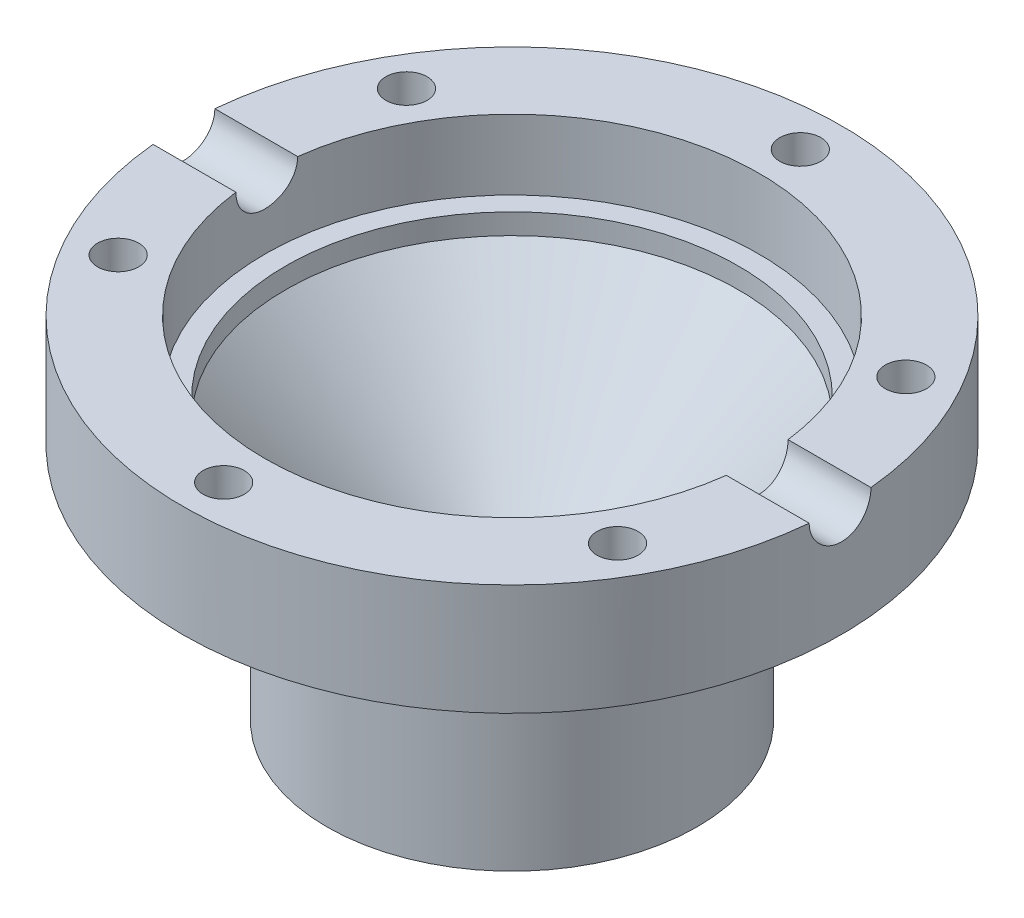
SolidWorks part; units mm, degrees
ref_plane "Front Plane" through (0, 0, 0) normal (0, 0, 1) x (1, 0, 0)
ref_plane "Top Plane" through (0, 0, 0) normal (0, 1, 0) x (1, 0, 0)
ref_plane "Right Plane" through (0, 0, 0) normal (1, 0, 0) x (0, 0, -1)
ref_axis "Centerline" through (0, 55, 0) along (0, -1, 0)
sketch "Sketch1" plane through (0, 0, 0) normal (0, 1, 0) x (1, 0, 0)
  circle A0 centre (0, 0) radius 20.32
  dimension "D1" = 40.64
extrude "Boss-Extrude1" add sketch "Sketch1" along normal blind 21.59
sketch "Sketch2" plane through (0, 0, 0) normal (0, 0, 1) x (1, 0, 0)
  line L0 (0, 26.2246) -> (0, -7.0612) construction
  line L5 (20.32, 21.59) -> (-20.32, 21.59) construction
  line L6 (0, 21.59) -> (-15.24, 21.59)
  line L7 (0, 21.59) -> (0, 17.272)
  line L8 (0, 17.272) -> (-15.24, 17.272)
  line L9 (-15.24, 21.59) -> (-15.24, 17.272)
  line L10 (-20.32, 21.59) -> (-20.32, 0) construction
  dimension "D1" = 5.08
  dimension "D2" = 4.318
revolve "Cut-Revolve1" cut sketch "Sketch2" angle 360 about axis through (0, 55, 0) along (0, -1, 0)
sketch "Sketch3" plane through (0, 0, 0) normal (0, 0, 1) x (1, 0, 0)
  line L0 (-20.32, 0) -> (20.32, 0) construction
  line L1 (-20.32, 14.732) -> (-15.24, 14.732)
  line L2 (-20.32, 14.732) -> (-20.32, 0)
  line L3 (-20.32, 0) -> (-15.24, 0)
  line L4 (-15.24, 14.732) -> (-15.24, 0)
  line L5 (20.32, 21.59) -> (-20.32, 21.59) construction
  line L6 (-20.32, 21.59) -> (-20.32, 0) construction
  dimension "D1" = 6.858
  dimension "D2" = 5.08
revolve "Cut-Revolve2" cut sketch "Sketch3" angle 360 about axis through (0, 55, 0) along (0, -1, 0)
sketch "Sketch4" plane through (0, 21.59, 0) normal (0, 1, 0) x (1, 0, 0)
  line L0 (0, 29.0947) -> (0, -35.1526) construction
  circle A0 centre (0, 17.78) radius 1.27
  dimension "D1" = 2.54
  dimension "D2" = 17.78
extrude "Cut-Extrude1" cut sketch "Sketch4" against normal up to next
pattern_circular "CirPattern1" count 6 over 360 about axis through (0, 0, 0) along (0, 1, 0) of "Cut-Extrude1"
sketch "Sketch5" plane through (0, 0, 0) normal (0, -1, 0) x (1, 0, 0)
  circle A0 centre (0, 0) radius 4.699
  dimension "D1" = 9.398
extrude "Cut-Extrude2" cut sketch "Sketch5" against normal up to next
sketch "Sketch7" plane through (0, 0, 0) normal (0, 0, 1) x (1, 0, 0)
  line L0 (-19.3213, 14.732) -> (23.1214, 14.732) construction
  line L1 (-20.32, 14.732) -> (20.32, 14.732) construction
  line L2 (-15.24, 14.732) -> (-15.24, 25.6293) construction
  line L4 (-15.24, 14.732) -> (-11.4097, 10.9017)
  line L5 (-11.4097, 10.9017) -> (-11.4097, 0)
  line L6 (-15.24, 0) -> (15.24, 0) construction
  line L7 (-11.4097, 0) -> (-15.24, 0)
  line L9 (-15.24, 14.732) -> (-15.24, 0)
  dimension "D1" = 45
  dimension "D2" = 10.9017
revolve "Cut-Revolve3" cut sketch "Sketch7" angle 360 about axis through (0, 55, 0) along (0, -1, 0)
sketch "Sketch8" plane through (0, 0, 0) normal (0, 0, 1) x (1, 0, 0)
  line L0 (-4.699, 24.8968) -> (-4.699, 18.7411) construction
  line L1 (-15.24, 24.5608) -> (-15.24, -3.2139) construction
  line L2 (15.24, 17.272) -> (-15.24, 17.272) construction
  line L3 (-4.699, 17.272) -> (-13.97, 17.272)
  line L4 (-13.97, 16.002) -> (-4.699, 6.731)
  line L5 (-22.2629, 0) -> (17.7783, 0) construction
  line L6 (-4.699, 6.731) -> (-4.699, 17.272)
  line L7 (-4.699, 17.272) -> (-4.699, -4.4972) construction
  line L8 (-13.97, 17.272) -> (-13.97, 16.002)
  line L9 (-13.97, 16.002) -> (-15.24, 17.272) construction
  line L10 (-15.24, 17.272) -> (-13.97, 17.272) construction
  dimension "D1" = 4.699
  dimension "D2" = 15.24
  dimension "D3" = 45
  dimension "D4" = 1.27
revolve "Cut-Revolve4" cut sketch "Sketch8" angle 360 about axis through (0, 55, 0) along (0, -1, 0)
ref_plane "Inlet Plane" through (20.32, 0, 0) normal (1, 0, 0) x (0, 0, -1)
sketch "Sketch9" plane through (20.32, 0, 0) normal (1, 0, 0) x (0, 0, -1)
  line L0 (0, 25.9244) -> (0, -6.8119) construction
  line L1 (20.32, 21.59) -> (-20.32, 21.59) construction
  circle A0 centre (0, 21.59) radius 1.905
  dimension "D1" = 3.81
extrude "Cut-Extrude3" cut sketch "Sketch9" against normal through all
